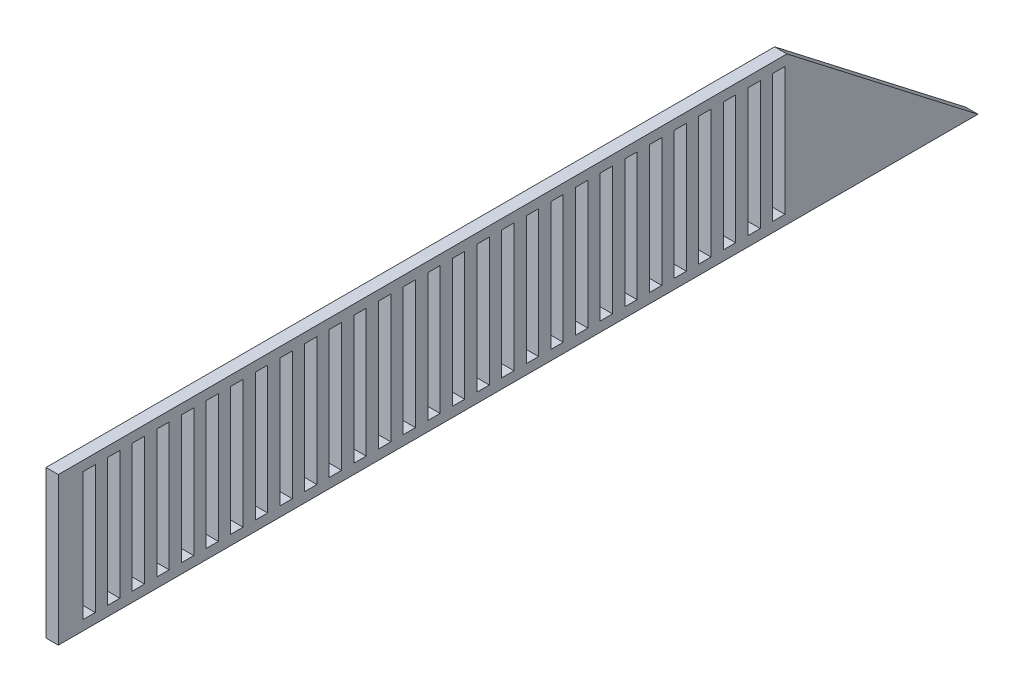
SolidWorks part; units mm, degrees
ref_plane "Front Plane" through (0, 0, 0) normal (0, 0, 1) x (1, 0, 0)
ref_plane "Top Plane" through (0, 0, 0) normal (0, 1, 0) x (1, 0, 0)
ref_plane "Right Plane" through (0, 0, 0) normal (1, 0, 0) x (0, 0, -1)
sketch "Sketch1" plane through (0, 0, 0) normal (1, 0, 0) x (0, 0, -1)
  line L0 (-237.109, 0) -> (237.109, 0)
  line L1 (-237.109, 0) -> (-237.109, 76.2)
  line L3 (-237.109, 76.2) -> (138.5888, 76.2)
  line L4 (-211.709, 71.12) -> (-205.359, 71.12)
  line L5 (-224.409, 71.12) -> (-218.059, 71.12)
  line L6 (-224.409, 71.12) -> (-224.409, 5.08)
  line L7 (-224.409, 5.08) -> (-218.059, 5.08)
  line L8 (-218.059, 71.12) -> (-218.059, 5.08)
  line L9 (-224.409, 71.12) -> (-218.059, 5.08) construction
  line L10 (-224.409, 5.08) -> (-218.059, 71.12) construction
  line L11 (-211.709, 71.12) -> (-211.709, 5.08)
  line L12 (-211.709, 5.08) -> (-205.359, 5.08)
  line L13 (-205.359, 71.12) -> (-205.359, 5.08)
  line L14 (-199.009, 71.12) -> (-192.659, 71.12)
  line L15 (-199.009, 71.12) -> (-199.009, 5.08)
  line L16 (-199.009, 5.08) -> (-192.659, 5.08)
  line L17 (-192.659, 71.12) -> (-192.659, 5.08)
  line L18 (-186.309, 71.12) -> (-179.959, 71.12)
  line L19 (-186.309, 71.12) -> (-186.309, 5.08)
  line L20 (-186.309, 5.08) -> (-179.959, 5.08)
  line L21 (-179.959, 71.12) -> (-179.959, 5.08)
  line L22 (-173.609, 71.12) -> (-167.259, 71.12)
  line L23 (-173.609, 71.12) -> (-173.609, 5.08)
  line L24 (-173.609, 5.08) -> (-167.259, 5.08)
  line L25 (-167.259, 71.12) -> (-167.259, 5.08)
  line L26 (-160.909, 71.12) -> (-154.559, 71.12)
  line L27 (-160.909, 71.12) -> (-160.909, 5.08)
  line L28 (-160.909, 5.08) -> (-154.559, 5.08)
  line L29 (-154.559, 71.12) -> (-154.559, 5.08)
  line L30 (-148.209, 71.12) -> (-141.859, 71.12)
  line L31 (-148.209, 71.12) -> (-148.209, 5.08)
  line L32 (-148.209, 5.08) -> (-141.859, 5.08)
  line L33 (-141.859, 71.12) -> (-141.859, 5.08)
  line L34 (-135.509, 71.12) -> (-129.159, 71.12)
  line L35 (-135.509, 71.12) -> (-135.509, 5.08)
  line L36 (-135.509, 5.08) -> (-129.159, 5.08)
  line L37 (-129.159, 71.12) -> (-129.159, 5.08)
  line L38 (-122.809, 71.12) -> (-116.459, 71.12)
  line L39 (-122.809, 71.12) -> (-122.809, 5.08)
  line L40 (-122.809, 5.08) -> (-116.459, 5.08)
  line L41 (-116.459, 71.12) -> (-116.459, 5.08)
  line L42 (-110.109, 71.12) -> (-103.759, 71.12)
  line L43 (-110.109, 71.12) -> (-110.109, 5.08)
  line L44 (-110.109, 5.08) -> (-103.759, 5.08)
  line L45 (-103.759, 71.12) -> (-103.759, 5.08)
  line L46 (-97.409, 71.12) -> (-91.059, 71.12)
  line L47 (-97.409, 71.12) -> (-97.409, 5.08)
  line L48 (-97.409, 5.08) -> (-91.059, 5.08)
  line L49 (-91.059, 71.12) -> (-91.059, 5.08)
  line L50 (-84.709, 71.12) -> (-78.359, 71.12)
  line L51 (-84.709, 71.12) -> (-84.709, 5.08)
  line L52 (-84.709, 5.08) -> (-78.359, 5.08)
  line L53 (-78.359, 71.12) -> (-78.359, 5.08)
  line L54 (-72.009, 71.12) -> (-65.659, 71.12)
  line L55 (-72.009, 71.12) -> (-72.009, 5.08)
  line L56 (-72.009, 5.08) -> (-65.659, 5.08)
  line L57 (-65.659, 71.12) -> (-65.659, 5.08)
  line L58 (-59.309, 71.12) -> (-52.959, 71.12)
  line L59 (-59.309, 71.12) -> (-59.309, 5.08)
  line L60 (-59.309, 5.08) -> (-52.959, 5.08)
  line L61 (-52.959, 71.12) -> (-52.959, 5.08)
  line L62 (-46.609, 71.12) -> (-40.259, 71.12)
  line L63 (-46.609, 71.12) -> (-46.609, 5.08)
  line L64 (-46.609, 5.08) -> (-40.259, 5.08)
  line L65 (-40.259, 71.12) -> (-40.259, 5.08)
  line L66 (-33.909, 71.12) -> (-27.559, 71.12)
  line L67 (-33.909, 71.12) -> (-33.909, 5.08)
  line L68 (-33.909, 5.08) -> (-27.559, 5.08)
  line L69 (-27.559, 71.12) -> (-27.559, 5.08)
  line L70 (-21.209, 71.12) -> (-14.859, 71.12)
  line L71 (-21.209, 71.12) -> (-21.209, 5.08)
  line L72 (-21.209, 5.08) -> (-14.859, 5.08)
  line L73 (-14.859, 71.12) -> (-14.859, 5.08)
  line L74 (-8.509, 71.12) -> (-2.159, 71.12)
  line L75 (-8.509, 71.12) -> (-8.509, 5.08)
  line L76 (-8.509, 5.08) -> (-2.159, 5.08)
  line L77 (-2.159, 71.12) -> (-2.159, 5.08)
  line L78 (4.191, 71.12) -> (10.541, 71.12)
  line L79 (4.191, 71.12) -> (4.191, 5.08)
  line L80 (4.191, 5.08) -> (10.541, 5.08)
  line L81 (10.541, 71.12) -> (10.541, 5.08)
  line L82 (16.891, 71.12) -> (23.241, 71.12)
  line L83 (16.891, 71.12) -> (16.891, 5.08)
  line L84 (16.891, 5.08) -> (23.241, 5.08)
  line L85 (23.241, 71.12) -> (23.241, 5.08)
  line L86 (29.591, 71.12) -> (35.941, 71.12)
  line L87 (29.591, 71.12) -> (29.591, 5.08)
  line L88 (29.591, 5.08) -> (35.941, 5.08)
  line L89 (35.941, 71.12) -> (35.941, 5.08)
  line L90 (42.291, 71.12) -> (48.641, 71.12)
  line L91 (42.291, 71.12) -> (42.291, 5.08)
  line L92 (42.291, 5.08) -> (48.641, 5.08)
  line L93 (48.641, 71.12) -> (48.641, 5.08)
  line L94 (54.991, 71.12) -> (61.341, 71.12)
  line L95 (54.991, 71.12) -> (54.991, 5.08)
  line L96 (54.991, 5.08) -> (61.341, 5.08)
  line L97 (61.341, 71.12) -> (61.341, 5.08)
  line L98 (67.691, 71.12) -> (74.041, 71.12)
  line L99 (67.691, 71.12) -> (67.691, 5.08)
  line L100 (67.691, 5.08) -> (74.041, 5.08)
  line L101 (74.041, 71.12) -> (74.041, 5.08)
  line L102 (80.391, 71.12) -> (86.741, 71.12)
  line L103 (80.391, 71.12) -> (80.391, 5.08)
  line L104 (80.391, 5.08) -> (86.741, 5.08)
  line L105 (86.741, 71.12) -> (86.741, 5.08)
  line L106 (93.091, 71.12) -> (99.441, 71.12)
  line L107 (93.091, 71.12) -> (93.091, 5.08)
  line L108 (93.091, 5.08) -> (99.441, 5.08)
  line L109 (99.441, 71.12) -> (99.441, 5.08)
  line L110 (105.791, 71.12) -> (112.141, 71.12)
  line L111 (105.791, 71.12) -> (105.791, 5.08)
  line L112 (105.791, 5.08) -> (112.141, 5.08)
  line L113 (112.141, 71.12) -> (112.141, 5.08)
  line L114 (118.491, 71.12) -> (124.841, 71.12)
  line L115 (118.491, 71.12) -> (118.491, 5.08)
  line L116 (118.491, 5.08) -> (124.841, 5.08)
  line L117 (124.841, 71.12) -> (124.841, 5.08)
  line L118 (131.191, 71.12) -> (137.541, 71.12)
  line L119 (131.191, 71.12) -> (131.191, 5.08)
  line L120 (131.191, 5.08) -> (137.541, 5.08)
  line L121 (137.541, 71.12) -> (137.541, 5.08)
  line L143 (138.5888, 76.2) -> (237.109, 0)
  line L144 (194.691, 71.12) -> (201.041, 71.12) [skipped]
  line L145 (194.691, 71.12) -> (194.691, 5.08) [skipped]
  line L146 (194.691, 5.08) -> (201.041, 5.08) [skipped]
  line L147 (201.041, 71.12) -> (201.041, 5.08) [skipped]
  line L148 (143.891, 71.12) -> (150.241, 71.12) [skipped]
  line L149 (143.891, 71.12) -> (143.891, 5.08) [skipped]
  line L150 (150.241, 71.12) -> (150.241, 5.08) [skipped]
  line L151 (156.591, 71.12) -> (162.941, 71.12) [skipped]
  line L152 (156.591, 71.12) -> (156.591, 5.08) [skipped]
  line L153 (162.941, 71.12) -> (162.941, 5.08) [skipped]
  line L154 (169.291, 71.12) -> (175.641, 71.12) [skipped]
  line L155 (169.291, 71.12) -> (169.291, 5.08) [skipped]
  line L156 (175.641, 71.12) -> (175.641, 5.08) [skipped]
  line L157 (181.991, 71.12) -> (188.341, 71.12) [skipped]
  line L158 (181.991, 71.12) -> (181.991, 5.08) [skipped]
  line L159 (188.341, 71.12) -> (188.341, 5.08) [skipped]
  line L160 (143.891, 5.08) -> (150.241, 5.08) [skipped]
  line L161 (156.591, 5.08) -> (162.941, 5.08) [skipped]
  line L162 (169.291, 5.08) -> (175.641, 5.08) [skipped]
  line L163 (181.991, 5.08) -> (188.341, 5.08) [skipped]
  point P0 (-221.234, 38.1)
  point P4 (0, 0)
  dimension "D1" = 474.218
  dimension "D2" = 76.2
  dimension "D4" = 12.7
  dimension "D5" = 5.08
  dimension "D6" = 5.08
  dimension "D7" = 6.35
  dimension "D8" = 34
extrude "Boss-Extrude1" add sketch "Sketch1" against normal blind 6.35
